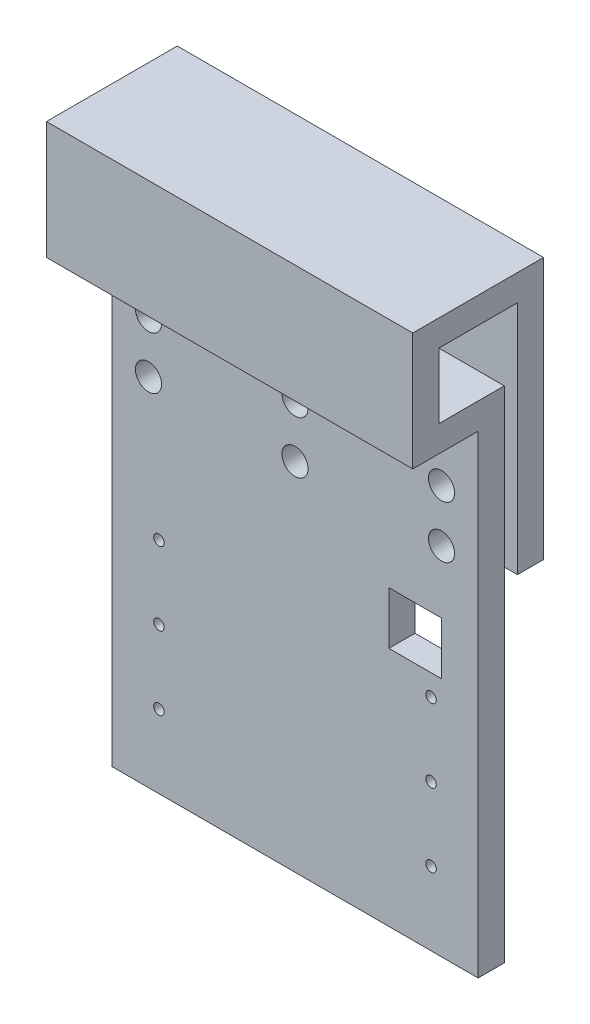
SolidWorks part; units mm, degrees
ref_plane "Front Plane" through (0, 0, 0) normal (0, 0, 1) x (1, 0, 0)
ref_plane "Top Plane" through (0, 0, 0) normal (0, 1, 0) x (1, 0, 0)
ref_plane "Right Plane" through (0, 0, 0) normal (1, 0, 0) x (0, 0, -1)
sketch "Sketch1" plane through (0, 0, 0) normal (1, 0, 0) x (0, 0, -1)
  line L0 (9.525, 8.255) -> (9.525, 65.405)
  line L1 (15.875, 8.255) -> (15.875, 71.755)
  line L2 (9.525, 65.405) -> (-9.525, 65.405)
  line L3 (-9.525, 65.405) -> (-9.525, 49.53)
  line L4 (-9.525, 49.53) -> (6.35, 49.53)
  line L5 (6.35, 49.53) -> (6.35, 11.43)
  line L6 (15.875, 71.755) -> (-15.875, 71.755)
  line L7 (-15.875, 71.755) -> (-15.875, 43.18)
  line L8 (-15.875, 43.18) -> (0, 43.18)
  line L9 (0, 43.18) -> (0, 11.43)
  line L10 (9.525, 8.255) -> (15.875, 8.255)
  line L11 (0, 11.43) -> (0, -71.755)
  line L12 (0, -71.755) -> (6.35, -71.755)
  line L13 (6.35, 11.43) -> (6.35, -71.755)
  line L14 (9.525, 8.255) -> (9.525, 40.005)
  line L15 (15.875, 8.255) -> (15.875, 40.005)
  point P0 (3.1856, 41.4486)
  dimension "D1" = 3.175
  dimension "D2" = 15.875
  dimension "D3" = 6.35
  dimension "D4" = 6.35
  dimension "D5" = 6.35
  dimension "D6" = 6.35
  dimension "D7" = 6.35
  dimension "D8" = 31.75
  dimension "D9" = 143.51
  dimension "D10" = 63.5
extrude "Boss-Extrude1" add sketch "Sketch1" along normal blind 88.9 contours L13 L5 L4 L3 L2 L0 L10 L1 L6 L7 L8 L9 L11 L12
sketch "Sketch2" plane through (0, 0, -15.875) normal (0, 0, -1) x (-1, 0, 0)
  line L0 (-88.9, 71.755) -> (0, 71.755) construction
  line L1 (-88.9, 8.255) -> (-88.9, 71.755) construction
  line L2 (-88.9, -71.755) -> (0, -71.755) construction
  line L3 (-80.01, -71.755) -> (-8.89, -71.755)
  line L4 (-80.01, -71.755) -> (-80.01, -0.5427)
  line L5 (-80.01, -0.5427) -> (-8.89, -0.5427)
  line L6 (-8.89, -71.755) -> (-8.89, -0.5427)
  line L7 (-80.01, -0.5427) -> (-67.2257, -0.5427)
  line L8 (-80.01, -0.5427) -> (-80.01, -13.3029)
  line L9 (-80.01, -13.3029) -> (-67.2257, -13.3029)
  line L10 (-67.2257, -0.5427) -> (-67.2257, -13.3029)
  circle A0 centre (-44.45, 27.305) radius 3.175
  circle A1 centre (-80.01, 27.305) radius 3.175
  circle A2 centre (-80.01, 14.605) radius 3.175
  circle A3 centre (-44.45, 14.605) radius 3.175
  circle A4 centre (-8.89, 14.605) radius 3.175
  circle A5 centre (-8.89, 27.305) radius 3.175
  circle A6 centre (-77.47, -18.415) radius 1.27
  circle A7 centre (-77.47, -36.195) radius 1.27
  circle A8 centre (-77.47, -53.975) radius 1.27
  circle A9 centre (-11.43, -53.975) radius 1.27
  circle A10 centre (-11.43, -36.195) radius 1.27
  circle A11 centre (-11.43, -18.415) radius 1.27
  point P22 (-44.45, -33.02)
  point P30 (-44.45, -33.02)
  dimension "D1" = 6.35
  dimension "D3" = 44.45
  dimension "D7" = 2.54
  dimension "D2" = 44.45
  dimension "D4" = 35.56
  dimension "D5" = 12.7
  dimension "D6" = 35.56
  dimension "D8" = 2.54
  dimension "D9" = 17.78
  dimension "D10" = 17.78
  dimension "D11" = 17.78
  dimension "D12" = 0
  dimension "D13" = 17.78
  dimension "D14" = 0
  dimension "D15" = 17.78
  dimension "D16" = 17.78
extrude "Cut-Extrude1" cut sketch "Sketch2" against normal blind 81.28 contours A1 | A0 | A5 | A4 | A3 | A2 | A11 | A10 | A9 | A8 | A7 | A6 | L8 L7 L10 L9
